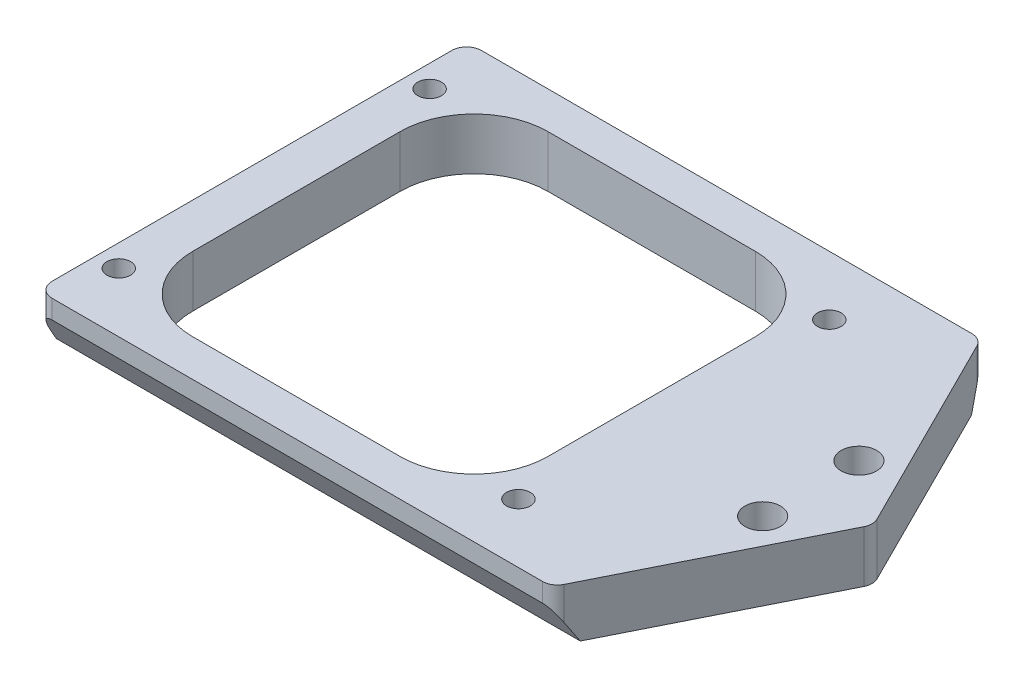
SolidWorks part; units mm, degrees
material "6061-T6 (SS)"
ref_plane "Front Plane" through (0, 0, 0) normal (0, 0, 1) x (1, 0, 0)
ref_plane "Top Plane" through (0, 0, 0) normal (0, 1, 0) x (1, 0, 0)
ref_plane "Right Plane" through (0, 0, 0) normal (1, 0, 0) x (0, 0, -1)
sketch "Sketch1" plane through (0, 0, 0) normal (0, 1, 0) x (1, 0, 0)
  line L0 (0, 14.5) -> (42, 14.5) construction
  line L1 (0, 0) -> (34.7484, 0)
  line L2 (0, 0) -> (0, 29)
  line L5 (42, 14.5) -> (34.7484, 29)
  line L6 (42, 14.5) -> (34.7484, 0)
  line L7 (0, 29) -> (34.7484, 29)
  dimension "D1" = 29
  dimension "D2" = 42
  dimension "D3" = 63.43
extrude "Boss-Extrude1" add sketch "Sketch1" along normal mid plane 3.5
sketch "Sketch2" plane through (0, 0, 0) normal (0, 1, 0) x (1, 0, 0)
  line L0 (0, 29) -> (0, 0) construction
  line L1 (3, 26.5) -> (27, 26.5)
  line L2 (3, 26.5) -> (3, 2.5)
  line L4 (27, 26.5) -> (27, 2.5)
  line L5 (0, 14.5) -> (42, 14.5) construction
  line L6 (34.7484, 29) -> (0, 29) construction
  line L7 (3, 2.5) -> (27, 2.5)
  point P14 (27, 14.5)
  point P15 (3, 14.5)
  dimension "D1" = 3
  dimension "D2" = 24
  dimension "D3" = 2.5
extrude "Cut-Extrude1" cut sketch "Sketch2" against normal through all both and the other way through all
fillet "Fillet1" radius 5 4 edges at (3, 0, -26.5) (27, 0, -26.5) (27, 0, -2.5) (3, 0, -2.5)
sketch "Sketch5" plane through (0, 1.75, 0) normal (0, 1, 0) x (1, 0, 0)
  line L0 (1.5, 25) -> (28.5, 25) construction
  line L1 (28.5, 25) -> (28.5, 4) construction
  line L2 (28.5, 4) -> (1.5, 4) construction
  line L3 (1.5, 4) -> (1.5, 25) construction
  line L4 (42, 14.5) -> (0, 14.5) construction
  line L8 (0, 29) -> (0, 0) construction
  point P8 (37.7484, 11.25)
  point P16 (37.7484, 17.75)
  dimension "D1" = 3.25
  dimension "D2" = 10.5
  dimension "D3" = 1.5
  dimension "D4" = 10.5
  dimension "D5" = 27
  dimension "D6" = 37.7484
hole_wizard "M2x0.4 Tapped Hole1" positions "3DSketch4" profile "Sketch8" tap size "M2x0.4" standard "ANSI Metric" end condition through all
sketch3d "3DSketch4"
  point P0 (1.5, 1.75, -25)
  point P3 (28.5, 1.75, -25)
  point P6 (37.7484, 1.75, -17.75)
  point P9 (37.7484, 1.75, -11.25)
  point P12 (28.5, 1.75, -4)
  point P15 (1.5, 1.75, -4)
  point P22 (0, 0, 0)
sketch "Sketch8" plane through (1.5, 1.75, -25) normal (1, 0, 0) x (0, 0, 1)
  line L0 (0, 0) -> (0, 3.5)
  line L1 (0, 3.5) -> (0.8, 3.5)
  line L2 (0.8, 3.5) -> (0.8, 0)
  line L5 (0.8, 0) -> (0, 0)
  line L11 (0, -6.35) -> (0, 107.95) construction
  dimension "Thru Tap Drill Dia." = 1.6
  dimension "Thru Tap Drill Depth" = 3.5
cosmetic thread "Hole Thread1" parameters "D2"=2
cosmetic thread "Hole Thread2" parameters "D2"=2
cosmetic thread "Hole Thread3" parameters "D2"=2
cosmetic thread "Hole Thread4" parameters "D2"=2
cosmetic thread "Hole Thread5" parameters "D2"=2
cosmetic thread "Hole Thread6" parameters "D2"=2
sketch "Sketch9" plane through (0, 1.75, 0) normal (0, 1, 0) x (1, 0, 0)
  line L3 (0, 0) -> (34.7484, 0) construction
  line L5 (0, 29) -> (0, 0) construction
  point P0 (32.5, 16)
  point P1 (32.5, 6)
  dimension "D1" = 32.5
  dimension "D2" = 16
  dimension "D3" = 6
  dimension "D4" = 32.5
hole_wizard "Ø1.5mm Dowel Hole1" positions "3DSketch5" profile "Sketch10" hole size "Ø1.5" standard "ANSI Metric"
sketch3d "3DSketch5"
  point P0 (32.5, 1.5, -16)
  point P3 (32.5, 1.5, -6)
sketch "Sketch10" plane through (32.5, 1.5, -16) normal (1, 0, 0) x (0, 0, 1)
  line L0 (0, 0) -> (0, 3)
  line L1 (0, 3) -> (0.75, 3)
  line L2 (0.75, 3) -> (0.75, 0)
  line L5 (0.75, 0) -> (0, 0)
  line L11 (0, -6.35) -> (0, 107.95) construction
  dimension "Thru Hole Dia." = 1.5
  dimension "Thru Hole Depth" = 3
fillet "Fillet2" radius 1 5 edges at (0, 0, -29) (34.7484, 0, -29) (42, 0, -14.5) (34.7484, 0, 0) (0, 0, 0)
sketch "Sketch11" plane through (0, 0.1199, -0.2076) normal (0, -0.5, 0.866) x (1, 0, 0)
  line L1 (39.154, -2.1591) -> (0, -2.1591)
  line L2 (39.154, -2.1591) -> (39.154, 1.488)
  line L3 (39.154, 1.488) -> (0, 1.488)
  line L4 (0, -2.1591) -> (0, 1.488)
extrude "Cut-Extrude2" cut sketch "Sketch11" along normal through all
ref_plane "Plane1" through (0, 0, -14.5) normal (0, 0, -1) x (-1, 0, 0)
mirror "Mirror1" about plane through (0, 0, -14.5) normal (0, 0, -1) of "Cut-Extrude2"
hole_wizard "M2 Clearance Hole2" positions "3DSketch7" profile "Sketch13" hole size "M2" standard "ANSI Metric" end condition through all
sketch3d "3DSketch7"
  line L0 (37.7484, -1.75, -17.75) -> (37.7484, 1.75, -17.75) construction
  line L1 (37.7484, -1.75, -11.25) -> (37.7484, 1.75, -11.25) construction
  point P0 (37.7484, 1.75, -17.75)
  point P4 (37.7484, 1.75, -11.25)
sketch "Sketch13" plane through (37.7484, 1.75, -17.75) normal (1, 0, 0) x (0, 0, 1)
  line L0 (0, 0) -> (0, 3.5)
  line L1 (0, 3.5) -> (1.2, 3.5)
  line L2 (1.2, 3.5) -> (1.2, 0)
  line L5 (1.2, 0) -> (0, 0)
  line L11 (0, -6.35) -> (0, 107.95) construction
  dimension "Thru Hole Dia." = 2.4
  dimension "Thru Hole Depth" = 3.5
